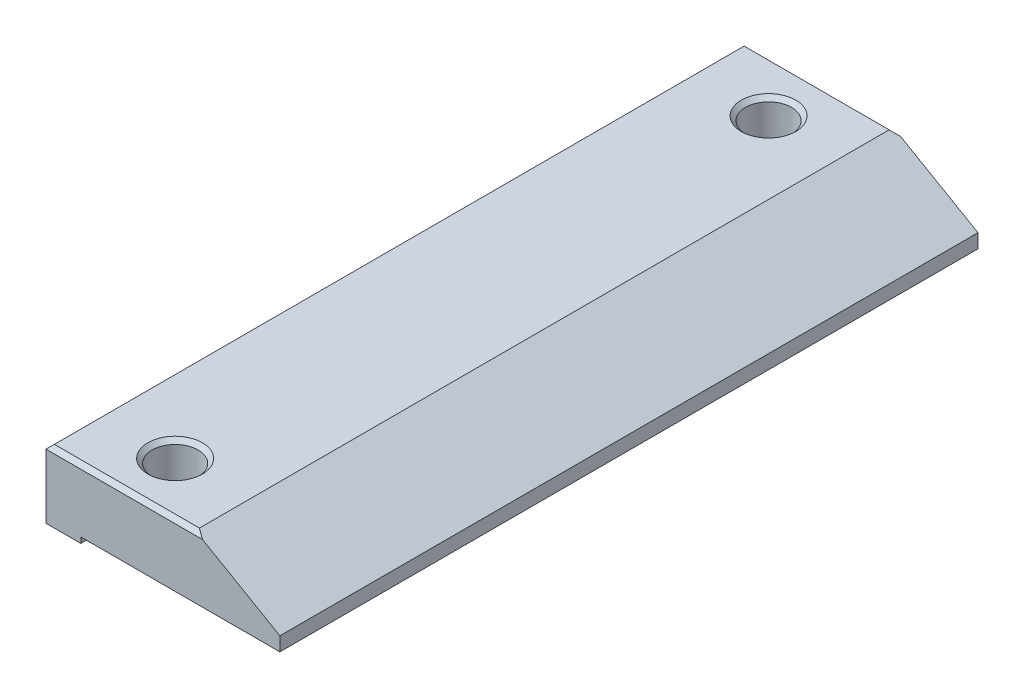
SolidWorks part; units mm, degrees
ref_plane "Front Plane" through (0, 0, 0) normal (0, 0, 1) x (1, 0, 0)
ref_plane "Top Plane" through (0, 0, 0) normal (0, 1, 0) x (1, 0, 0)
ref_plane "Right Plane" through (0, 0, 0) normal (1, 0, 0) x (0, 0, -1)
sketch "Sketch1" plane through (0, 0, 0) normal (0, 0, 1) x (1, 0, 0)
  line L0 (-61, 0) -> (-56, 0)
  line L1 (-32.5, 0.8) -> (32.5, 0.8) construction
  line L2 (-32.5, 0.8) -> (-32.5, 0) construction
  line L3 (-32.5, 0) -> (32.5, 0) construction
  line L4 (32.5, 0.8) -> (32.5, 0) construction
  line L5 (-56, 0) -> (-56, 0.8)
  line L6 (-56, 0.8) -> (-27.5, 0.8)
  line L7 (-27.5, 0.8) -> (-27.5, 2.8)
  line L8 (-27.5, 2.8) -> (-39.6244, 9.8)
  line L9 (-39.6244, 9.8) -> (-61, 9.8)
  line L10 (-61, 9.8) -> (-61, 0)
  line L11 (-53, 9.8) -> (-53, 0.8) construction
  line L12 (-47, 9.8) -> (-47, 0.8) construction
  line L13 (-53, 5.3) -> (-47, 5.3) construction
  point P18 (-50, 5.3)
  dimension "D1" = 0.8
  dimension "D2" = 65
  dimension "D3" = 50
  dimension "D4" = 6
  dimension "D5" = 3
  dimension "D6" = 5
  dimension "D7" = 5
  dimension "D8" = 30
  dimension "D9" = 9
  dimension "D10" = 2
extrude "Boss-Extrude1" add sketch "Sketch1" along normal blind 100
hole_wizard "M6 Clearance Hole2" positions "Sketch2" profile "Sketch3" hole size "M6" standard "ANSI Metric" end condition through all
sketch "Sketch2" plane through (0, 9.8, 0) normal (0, 1, 0) x (1, 0, 0)
  line L0 (-50, -7.5) -> (-50, -92.5) construction
  line L2 (-39.6244, -100) -> (-61, -100) construction
  line L3 (-39.6244, 0) -> (-61, 0) construction
  circle A0 centre (-50, -7.5) radius 7.5 construction
  circle A1 centre (-50, -92.5) radius 7.5 construction
  point P1 (-50, -7.5)
  point P6 (-50, -92.5)
  point P21 (-50, -7.5)
  point P23 (-50, -92.5)
  dimension "D1" = 15
sketch "Sketch3" plane through (-50, 9.8, 92.5) normal (1, 0, 0) x (0, 0, 1)
  line L0 (0, 0) -> (0, 9.8)
  line L1 (0, 9.8) -> (3.3, 9.8)
  line L2 (3.3, 9.8) -> (3.3, 0)
  line L5 (3.3, 0) -> (0, 0)
  line L11 (0, -6.35) -> (0, 107.95) construction
  dimension "Thru Hole Dia." = 6.6
  dimension "Thru Hole Depth" = 9.8
chamfer "Chamfer1" distance 0.6 angle 45 5 edges at (-50, 9.8, 10.8) (-50, 9.8, 95.8) (-50.3122, 9.8, 0) (-61, 9.8, 50) (-50.3122, 9.8, 100)
